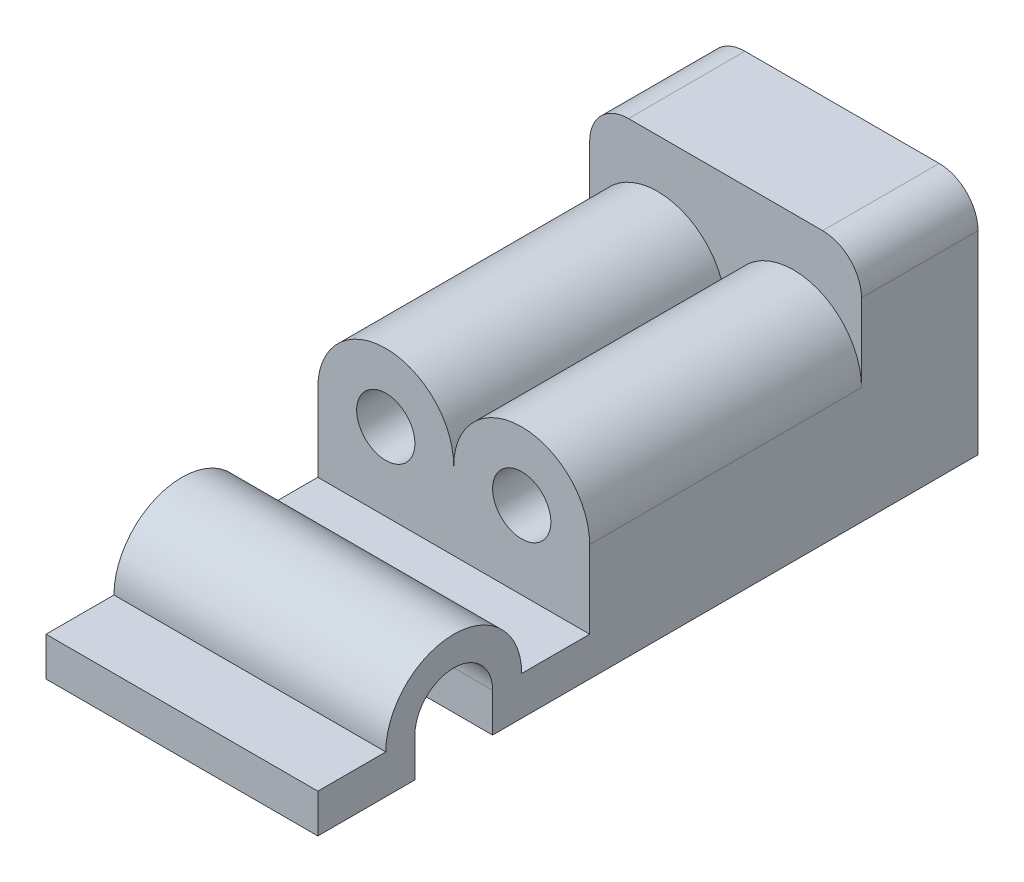
SolidWorks part; units mm, degrees
ref_plane "Front Plane" through (0, 0, 0) normal (0, 0, 1) x (1, 0, 0)
ref_plane "Top Plane" through (0, 0, 0) normal (0, 1, 0) x (1, 0, 0)
ref_plane "Right Plane" through (0, 0, 0) normal (1, 0, 0) x (0, 0, -1)
sketch "Sketch2" plane through (0, 0, 0) normal (0, 0, 1) x (1, 0, 0)
  line L0 (-35, 0) -> (35, 0)
  line L1 (-35, 0) -> (-35, 60)
  line L2 (-35, 60) -> (35, 60)
  line L3 (35, 60) -> (35, 0)
  point P4 (0, 0)
  dimension "D1" = 70
  dimension "D2" = 60
extrude "Boss-Extrude1" add sketch "Sketch2" along normal blind 100
sketch "Sketch3" plane through (0, 0, 100) normal (0, 0, 1) x (1, 0, 0)
  line L0 (35, 60) -> (-35, 60) construction
  line L1 (35, 60) -> (-35, 60)
  line L2 (0, 0) -> (0, 60) construction
  line L3 (-35, 0) -> (35, 0) construction
  line L4 (-35, 60) -> (-35, 0) construction
  line L5 (-35, 30) -> (0, 30) construction
  line L6 (35, 0) -> (35, 60) construction
  line L7 (35, 30) -> (35, 60)
  line L8 (-35, 60) -> (-35, 30)
  arc A0 (0, 30) -> (-35, 30) centre (-17.5, 30) ccw
  circle A1 centre (-17.5, 30) radius 7.5
  circle A2 centre (17.5, 30) radius 7.5
  arc A3 (0, 30) -> (35, 30) centre (17.5, 30) cw
  dimension "D3" = 15
  dimension "D1" = 30
extrude "Cut-Extrude1" cut sketch "Sketch3" against normal blind 70
sketch "Sketch4" plane through (-35, 0, 0) normal (-1, 0, 0) x (0, 0, 1)
  line L0 (100, 0) -> (125, 0)
  line L1 (0, 60) -> (0, 0) construction
  line L2 (125, 10) -> (125, 0)
  line L3 (145, 10) -> (145, 0)
  line L4 (145, 0) -> (170, 0)
  line L5 (117.5, 10) -> (152.5, 10) construction
  line L6 (152.5, 10) -> (170, 10)
  line L7 (170, 10) -> (170, 0)
  line L8 (117.5, 10) -> (100, 10)
  line L9 (100, 30) -> (100, 0) construction
  line L10 (100, 10) -> (100, 0)
  arc A0 (145, 10) -> (125, 10) centre (135, 10) ccw
  arc A1 (152.5, 10) -> (117.5, 10) centre (135, 10) ccw
  dimension "D2" = 20
  dimension "D5" = 35
  dimension "D1" = 125
  dimension "D3" = 10
  dimension "D4" = 35
extrude "Boss-Extrude2" add sketch "Sketch4" against normal up to surface (70 mm away) up to face at (35, 30, 43.3333)
fillet "Fillet1" radius 10 2 edges at (35, 60, 15) (-35, 60, 15)
